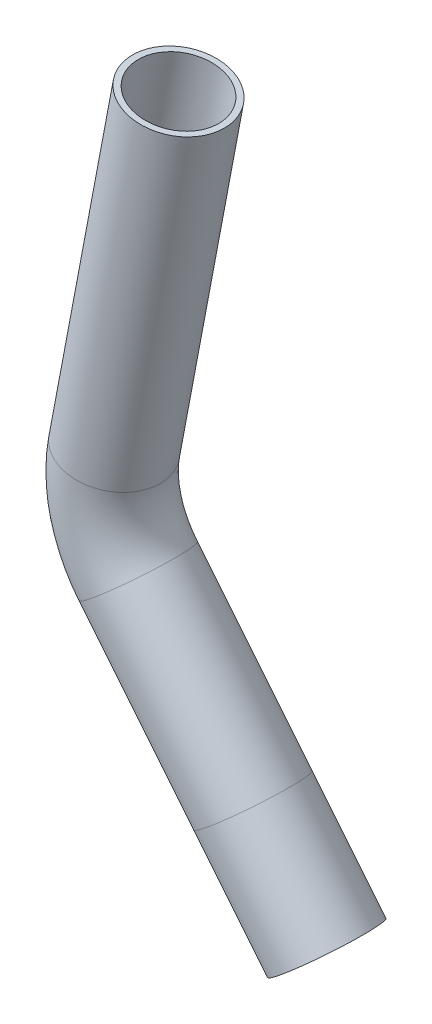
SolidWorks part; units mm, degrees
ref_plane "Спереди" through (0, 0, 0) normal (0, 0, 1) x (1, 0, 0)
ref_plane "Сверху" through (0, 0, 0) normal (0, 1, 0) x (1, 0, 0)
ref_plane "Справа" through (0, 0, 0) normal (1, 0, 0) x (0, 0, -1)
sketch "Эскиз1" plane through (0, 0, 0) normal (0, 0, 1) x (1, 0, 0)
  line L0 (-6.3059, 7.7611) -> (-16.1072, 19.8242)
  line L1 (-18.1715, 27.9903) -> (-12.6706, 57.0465)
  line L2 (-6.3059, 7.7611) -> (0, 0)
  arc A0 (-16.1072, 19.8242) -> (-18.1715, 27.9903) centre (-8.346, 26.1302) cw
  dimension "D1" = 10
ref_plane "Плоскость1" through (0, 0, 0) normal (0.6306, -0.7761, 0) x (-0.7761, -0.6306, 0)
sketch "Эскиз2" plane through (0, 0, 0) normal (0.6306, -0.7761, 0) x (-0.7761, -0.6306, 0)
  circle A0 centre (0, 0) radius 4
  circle A1 centre (0, 0) radius 3.5
sweep "По траектории1" add profiles "Эскиз2" path "Эскиз1"
